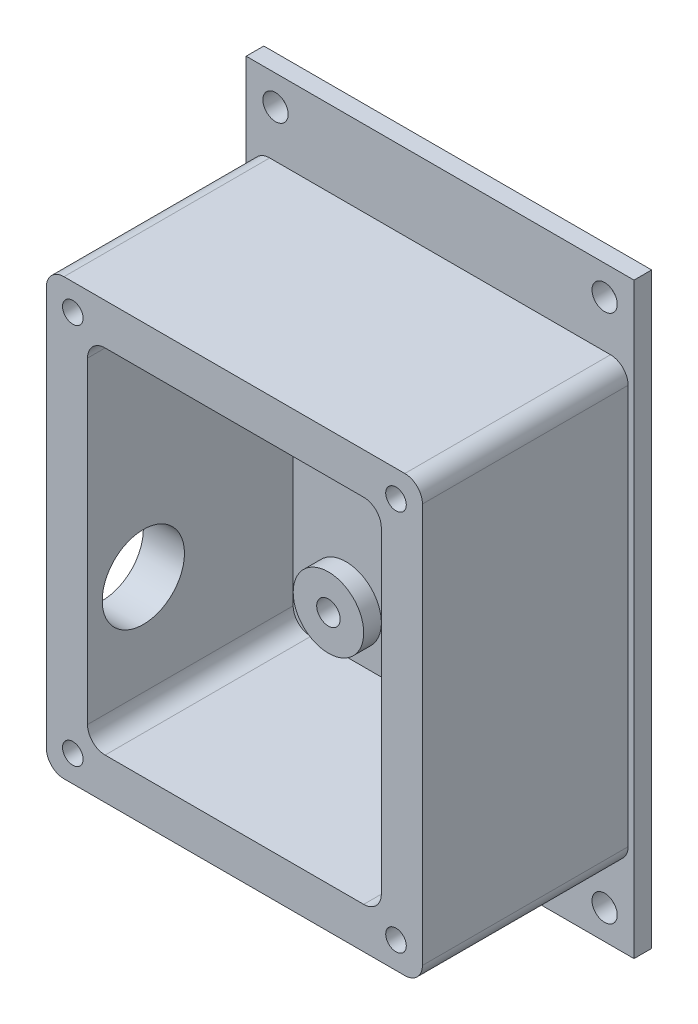
SolidWorks part; units mm, degrees
ref_plane "Přední rovina" through (0, 0, 0) normal (0, 0, 1) x (1, 0, 0)
ref_plane "Horní rovina" through (0, 0, 0) normal (0, 1, 0) x (1, 0, 0)
ref_plane "Pravá rovina" through (0, 0, 0) normal (1, 0, 0) x (0, 0, -1)
sketch "Skica1" plane through (0, 0, 0) normal (0, 0, 1) x (1, 0, 0)
  line L1 (0, 0) -> (50, 0)
  line L2 (0, 0) -> (0, 60)
  line L3 (0, 60) -> (50, 60)
  line L4 (50, 0) -> (50, 60)
  dimension "D1" = 60
  dimension "D2" = 50
extrude "Přidat vysunutím2" add sketch "Skica1" along normal blind 3 contours L3 L4 L1 L2
sketch "Skica2" plane through (0, 0, 3) normal (0, 0, 1) x (1, 0, 0)
  line L0 (0, 60) -> (50, 60) construction
  line L1 (0, 0) -> (0, 60) construction
  line L2 (9, 53) -> (35, 53) construction
  line L3 (50, 0) -> (50, 60) construction
  line L5 (9, 8) -> (9, 53) construction
  line L6 (9, 53) -> (35, 53) construction
  line L7 (35, 53) -> (35, 8) construction
  line L8 (35, 8) -> (9, 8) construction
  line L9 (0, 0) -> (50, 0) construction
  line L10 (9, 8) -> (0, 8) construction
  circle A0 centre (9, 53) radius 2
  circle A1 centre (35, 53) radius 2
  circle A2 centre (35, 8) radius 2
  circle A3 centre (9, 8) radius 2
  point P18 (9, 56.9985)
  point P20 (9, 4.021)
  dimension "D1" = 4
  dimension "D9" = 8
  dimension "D2" = 7
  dimension "D3" = 9
  dimension "D6" = 26
  dimension "D7" = 15
  dimension "D8" = 45
  dimension "D10" = 9
  dimension "D4" = 2
  dimension "D5" = 2
sketch "Skica3" plane through (0, 0, 3) normal (0, 0, 1) x (1, 0, 0)
  line L3 (0, 0) -> (50, 0) construction
  line L4 (0, 60) -> (50, 60) construction
  line L5 (0, 0) -> (0, 60) construction
  line L6 (50, 0) -> (50, 60) construction
  line L11 (0, 60) -> (50, 60)
  line L12 (0, 60) -> (0, 0)
  line L13 (0, 0) -> (50, 0)
  line L14 (50, 60) -> (50, 0)
extrude "Vysunout tenkostěnný1" add sketch "Skica3" along normal blind 35 separate body thin thin type one direction wall 7
sketch "Skica4" plane through (0, 0, 0) normal (0, 0, -1) x (-1, 0, 0)
  line L8 (-53, 75) -> (3, 75) construction
  line L9 (0, 60) -> (-50, 60) construction
  line L10 (7, 67) -> (7, -7) construction
  line L11 (8, 80) -> (8, -20)
  line L12 (-58, -20) -> (8, -20)
  line L13 (-58, 80) -> (-58, -20)
  line L14 (-58, 80) -> (8, 80)
  line L16 (-50, 60) -> (0, 60)
  line L17 (-50, 60) -> (-50, 0)
  line L18 (-50, 0) -> (0, 0)
  line L19 (0, 60) -> (0, 0)
  line L21 (0, 0) -> (-50, 0) construction
  line L22 (-50, 0) -> (-50, 60) construction
  line L23 (-57, -7) -> (-57, 67) construction
  circle A0 centre (-53, 75) radius 2.15
  circle A1 centre (3, 75) radius 2.15
  circle A2 centre (3, -15) radius 2.15
  circle A3 centre (-53, -15) radius 2.15
  dimension "D2" = 4.3
  dimension "D9" = 20
  dimension "D10" = 5
  dimension "D11" = 5
  dimension "D7" = 5
  dimension "D12" = 1
  dimension "D3" = 5
  dimension "D4" = 5
  dimension "D8" = 20
  dimension "D14" = 1
  dimension "D5" = 2
  dimension "D6" = 2
extrude "Přidat vysunutím5" add sketch "Skica4" against normal blind 3
extrude "Vysunout tenkostěnný2" add sketch "Skica2" along normal blind 3 thin
fillet "Zaoblit2" radius 3 4 edges at (-7, -7, 20.5) (57, -7, 20.5) (57, 67, 20.5) (-7, 67, 20.5)
sketch "Skica9" plane through (0, 0, 0) normal (1, 0, 0) x (0, 0, -1)
  line L0 (-3, 60) -> (-3, 0) construction
  circle A0 centre (-28.5, 20) radius 7
  dimension "D1" = 14
  dimension "D2" = 25.5
extrude "Odebrat vysunutím3" cut sketch "Skica9" against normal up to next
sketch "Skica10" plane through (0, 0, 38) normal (0, 0, 1) x (1, 0, 0)
  line L0 (-2.5, 62.5) -> (52.5, 62.5) construction
  line L1 (-2.5, 62.5) -> (-2.5, -2.5) construction
  line L3 (54, 67) -> (-4, 67) construction
  line L4 (57, -4) -> (57, 64) construction
  circle A0 centre (-2.5, 62.5) radius 1.75
  circle A1 centre (52.5, 62.5) radius 1.75
  circle A2 centre (52.5, -2.5) radius 1.75
  circle A3 centre (-2.5, -2.5) radius 1.75
  dimension "D5" = 3.5
  dimension "D3" = 55
  dimension "D4" = 65
  dimension "D6" = 4.5
  dimension "D7" = 4.5
  dimension "D1" = 2
  dimension "D2" = 2
fillet "Zaoblit4" radius 3 1 edges at (50, 60, 20.5)
fillet "Zaoblit5" radius 3 1 edges at (50, 0, 20.5)
fillet "Zaoblit6" radius 3 1 edges at (0, 0, 20.5)
fillet "Zaoblit7" radius 3 1 edges at (0, 60, 20.5)
extrude "Odebrat vysunutím4" cut sketch "Skica10" against normal blind 30
